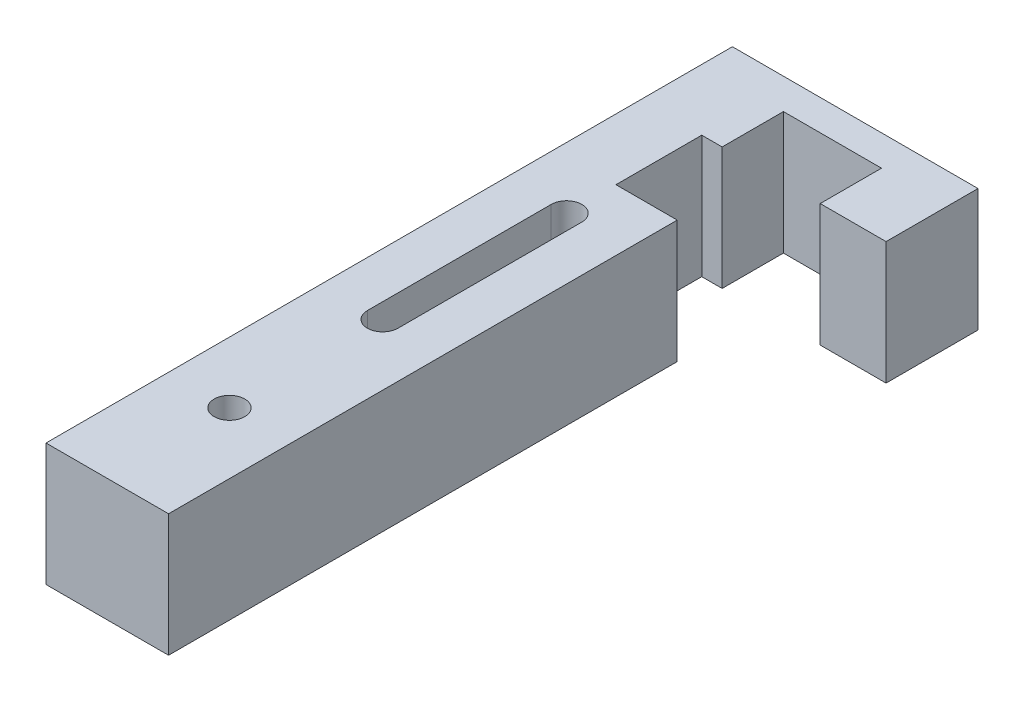
SolidWorks part; units mm, degrees
ref_plane "Front Plane" through (0, 0, 0) normal (0, 0, 1) x (1, 0, 0)
ref_plane "Top Plane" through (0, 0, 0) normal (0, 1, 0) x (1, 0, 0)
ref_plane "Right Plane" through (0, 0, 0) normal (1, 0, 0) x (0, 0, -1)
sketch "Sketch1" plane through (0, 0, 0) normal (0, 1, 0) x (1, 0, 0)
  line L1 (-12.7, -50.8) -> (12.7, -50.8)
  line L2 (-12.7, -50.8) -> (-12.7, 50.8)
  line L3 (-12.7, 50.8) -> (12.7, 50.8)
  line L4 (12.7, -50.8) -> (12.7, 50.8)
  line L5 (-12.7, -50.8) -> (12.7, 50.8) construction
  line L6 (-12.7, 50.8) -> (12.7, -50.8) construction
  point P0 (0, 0)
  dimension "D1" = 101.6
  dimension "D2" = 25.4
extrude "Boss-Extrude1" add sketch "Sketch1" along normal blind 25.4
sketch "Sketch2" plane through (0, 25.4, 0) normal (0, 1, 0) x (1, 0, 0)
  line L0 (0, 44.3696) -> (0, 6.2696) construction
  line L1 (0, -13.97) -> (0, 13.97) construction
  line L2 (3.175, 44.3696) -> (3.175, 6.2696)
  line L3 (-3.175, 44.3696) -> (-3.175, 6.2696)
  arc A0 (3.175, 44.3696) -> (-3.175, 44.3696) centre (0, 44.3696) ccw
  arc A1 (-3.175, 6.2696) -> (3.175, 6.2696) centre (0, 6.2696) ccw
  circle A2 centre (0, -25.4804) radius 3.175
  point P5 (0, 25.3196)
  point P12 (0, 15.058)
  point P13 (0, 44.3696)
  dimension "D3" = 6.35
  dimension "D1" = 6.35
  dimension "D2" = 38.1
  dimension "D4" = 69.85
extrude "Cut-Extrude1" cut sketch "Sketch2" against normal through all
sketch "Sketch3" plane through (0, 0, 0) normal (0, 1, 0) x (1, 0, 0)
  line L0 (-12.7, 50.8) -> (-12.7, 91.44)
  line L1 (-12.7, 91.44) -> (38.1967, 91.44)
  line L5 (38.1967, 72.39) -> (0, 72.39)
  line L7 (12.7, -50.8) -> (12.7, 50.8) construction
  line L8 (-12.7, 50.8) -> (12.7, 50.8)
  line L9 (0, 72.39) -> (0, 54.61)
  line L10 (0, 54.61) -> (12.7, 54.61)
  line L14 (38.1967, 91.44) -> (38.1967, 72.39)
  line L15 (12.7, 50.8) -> (12.7, 54.61)
  point P5 (12.7, 54.8912)
  dimension "D1" = 17.78
  dimension "D2" = 12.7
  dimension "D3" = 19.05
  dimension "D4" = 3.81
extrude "Boss-Extrude2" add sketch "Sketch3" along normal blind 25.4 contours L5 L9 L10 L15 L8 L0 L1 L14
sketch "Sketch4" plane through (0, 25.4, 0) normal (0, 1, 0) x (1, 0, 0)
  line L0 (38.1967, 72.39) -> (0, 72.39) construction
  line L1 (4.2277, 85.09) -> (24.5477, 85.09)
  line L2 (4.2277, 85.09) -> (4.2277, 72.39)
  line L3 (4.2277, 72.39) -> (24.5477, 72.39)
  line L4 (24.5477, 85.09) -> (24.5477, 72.39)
  line L5 (4.2277, 85.09) -> (24.5477, 72.39) construction
  line L6 (4.2277, 72.39) -> (24.5477, 85.09) construction
  point P0 (14.3877, 78.74)
  point P7 (11.2754, 80.9673)
  point P8 (19.2589, 81.28)
  point P9 (14.3877, 81.28)
  dimension "D1" = 20.32
  dimension "D2" = 12.7
extrude "Cut-Extrude2" cut sketch "Sketch4" against normal blind 152.4
